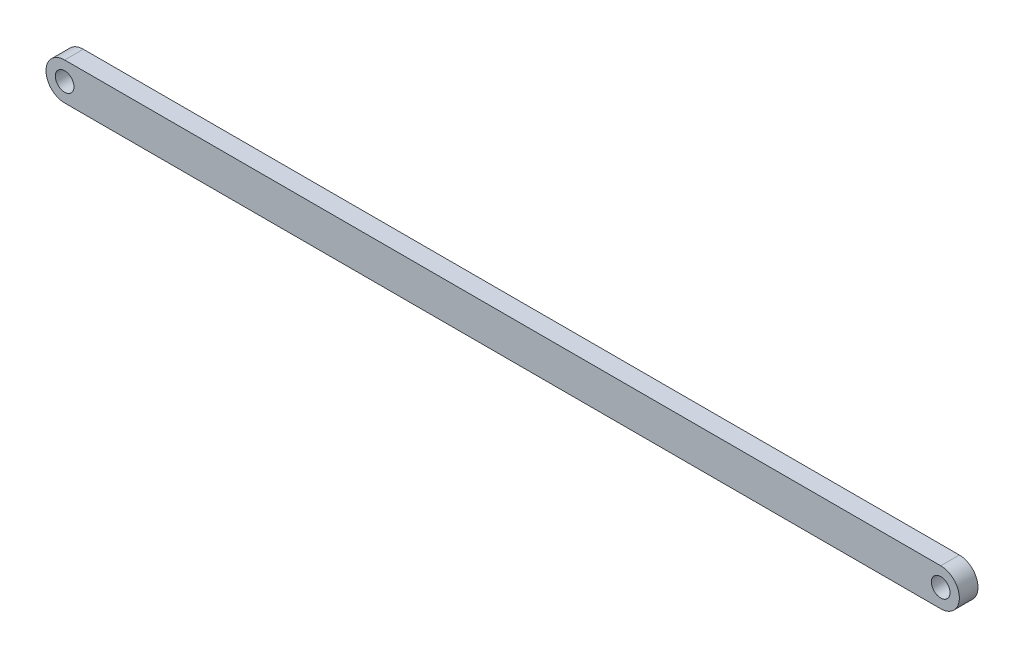
SolidWorks part; units mm, degrees
material "1023 碳钢板 (SS)"
ref_plane "前视基准面" through (0, 0, 0) normal (0, 0, 1) x (1, 0, 0)
ref_plane "上视基准面" through (0, 0, 0) normal (0, 1, 0) x (1, 0, 0)
ref_plane "右视基准面" through (0, 0, 0) normal (1, 0, 0) x (0, 0, -1)
sketch "草图1" plane through (0, 0, 0) normal (0, 0, 1) x (1, 0, 0)
  line L0 (0, 0) -> (2350, 0) construction
  line L1 (0, 50) -> (2350, 50)
  line L2 (0, -50) -> (2350, -50)
  arc A0 (0, 50) -> (0, -50) centre (0, 0) ccw
  arc A1 (2350, -50) -> (2350, 50) centre (2350, 0) ccw
  circle A2 centre (0, 0) radius 25
  circle A3 centre (2350, 0) radius 25
  point P2 (1175, 0)
  dimension "D3" = 50
  dimension "D1" = 2350
  dimension "D2" = 50
extrude "拉伸1" add sketch "草图1" along normal blind 50
